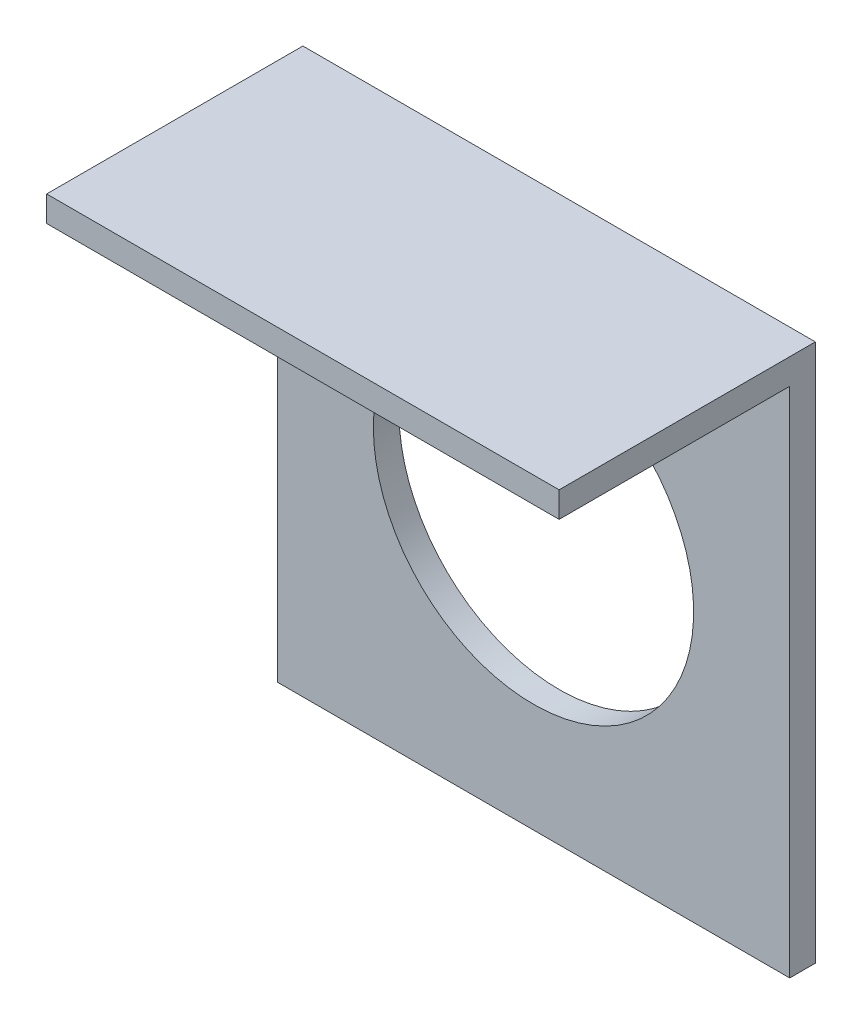
SolidWorks part; units mm, degrees
ref_plane "Front Plane" through (0, 0, 0) normal (0, 0, 1) x (1, 0, 0)
ref_plane "Top Plane" through (0, 0, 0) normal (0, 1, 0) x (1, 0, 0)
ref_plane "Right Plane" through (0, 0, 0) normal (1, 0, 0) x (0, 0, -1)
sketch "Sketch1" plane through (0, 0, 0) normal (0, 0, 1) x (1, 0, 0)
  line L1 (-20, -21) -> (20, -21)
  line L2 (-20, -21) -> (-20, 21)
  line L3 (-20, 21) -> (20, 21)
  line L4 (20, -21) -> (20, 21)
  line L5 (-20, -21) -> (20, 21) construction
  line L6 (-20, 21) -> (20, -21) construction
  circle A0 centre (0, 0) radius 12.5
  point P0 (0, 0)
  dimension "D3" = 25
  dimension "D1" = 40
  dimension "D2" = 42
extrude "Boss-Extrude1" add sketch "Sketch1" along normal blind 2
sketch "Sketch3" plane through (0, 0, 2) normal (0, 0, 1) x (1, 0, 0)
  line L0 (0, 21) -> (0, 9.738) construction
  line L1 (20, 21) -> (-20, 21) construction
  line L2 (20, -21) -> (20, 21) construction
  line L3 (-20, 21) -> (20, 21)
  line L4 (-20, 21) -> (-20, 19)
  line L5 (-20, 19) -> (20, 19)
  line L6 (20, 21) -> (20, 19)
  line L7 (-20, 21) -> (20, 19) construction
  line L8 (-20, 19) -> (20, 21) construction
  point P5 (0, 20)
  dimension "D1" = 2
  dimension "D2" = 1
extrude "Boss-Extrude2" add sketch "Sketch3" along normal blind 18
sketch "Sketch4" plane through (0, 0, 2) normal (0, 0, 1) x (1, 0, 0)
  circle A0 centre (0, 0) radius 12.5
  dimension "D1" = 25
extrude "Boss-Extrude3" add sketch "Sketch4" against normal blind 2
sketch "Sketch5" plane through (0, 0, 0) normal (0, 0, -1) x (-1, 0, 0)
  line L0 (-20, 21) -> (20, 21) construction
  circle A0 centre (0, 0) radius 12.5
  dimension "D1" = 25
  dimension "D2" = 21
extrude "Cut-Extrude1" cut sketch "Sketch5" against normal blind 2
sketch "Sketch6" plane through (0, 0, 0) normal (0, 0, -1) x (-1, 0, 0)
  line L0 (0, 21) -> (0, -21)
  line L1 (-20, 21) -> (20, 21) construction
  line L2 (20, -21) -> (-20, -21) construction
